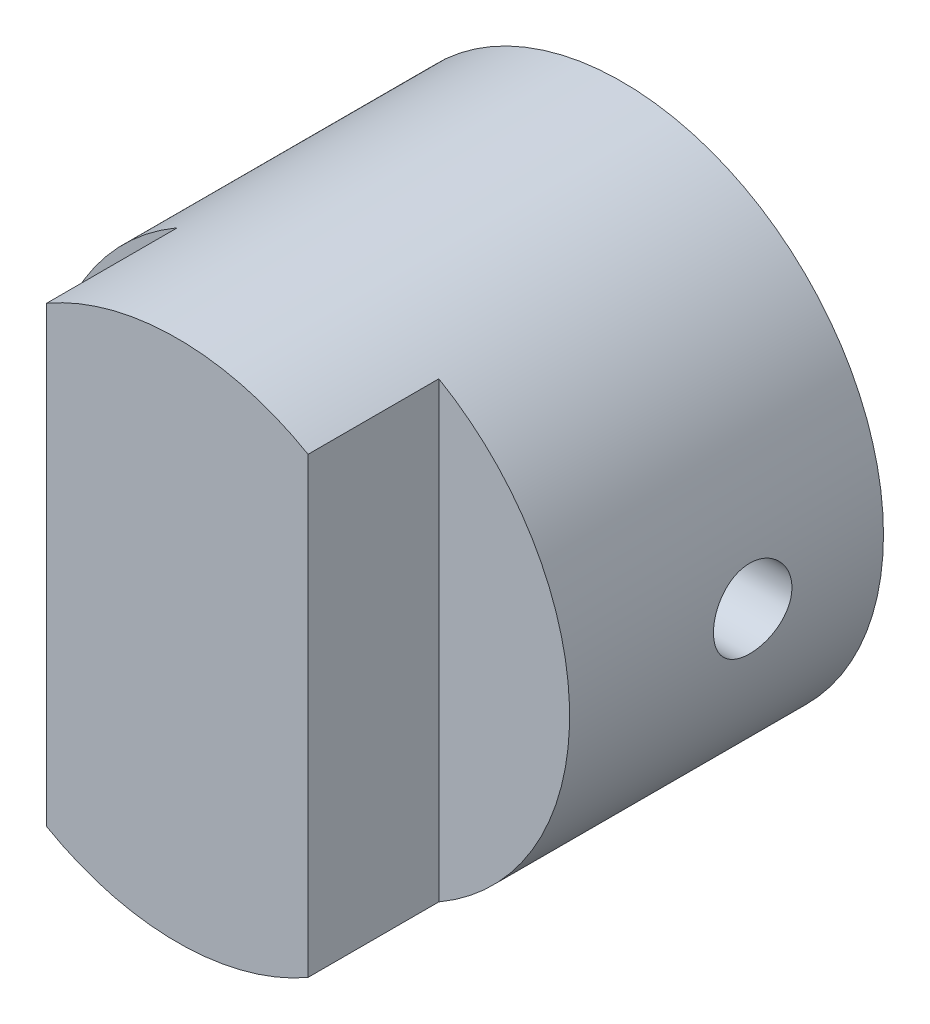
SolidWorks part; units mm, degrees
ref_plane "Plano frontal" through (0, 0, 0) normal (0, 0, 1) x (1, 0, 0)
ref_plane "Plano superior" through (0, 0, 0) normal (0, 1, 0) x (1, 0, 0)
ref_plane "Plano direito" through (0, 0, 0) normal (1, 0, 0) x (0, 0, -1)
sketch "Esboço1" plane through (0, 0, 0) normal (0, 0, 1) x (1, 0, 0)
  circle A0 centre (0, 0) radius 10
  dimension "D1" = 20
extrude "Ressalto-extrusão1" add sketch "Esboço1" along normal blind 17
sketch "Esboço4" plane through (0, 0, 0) normal (0, 0, -1) x (-1, 0, 0)
  circle A0 centre (0, 0) radius 7.5
  dimension "D1" = 15
extrude "Corte-extrusão3" cut sketch "Esboço4" against normal blind 10
sketch "Esboço2" plane through (0, 0, 17) normal (0, 0, 1) x (1, 0, 0)
  line L2 (-5, 8.6603) -> (-5, -8.6603)
  line L4 (5, 8.6603) -> (5, -8.6603)
  circle A0 centre (0, 0) radius 10 construction
  arc A1 (5, -8.6603) -> (5, 8.6603) centre (0, 0) ccw
  arc A2 (-5, 8.6603) -> (-5, -8.6603) centre (0, 0) ccw
  dimension "D1" = 5
  dimension "D2" = 5
extrude "Corte-extrusão1" cut sketch "Esboço2" against normal blind 5
sketch "Esboço5" plane through (5, 0, 0) normal (1, 0, 0) x (0, 0, -1)
  line L0 (-17, 0) -> (1.3165, 0) construction
  line L1 (-17, 8.6603) -> (-17, -8.6603) construction
  line L2 (0, -10) -> (0, 10) construction
  circle A0 centre (-5, 0) radius 1.5
  dimension "D1" = 5
  dimension "D2" = 3
extrude "Corte-extrusão4" cut sketch "Esboço5" along normal up to next
